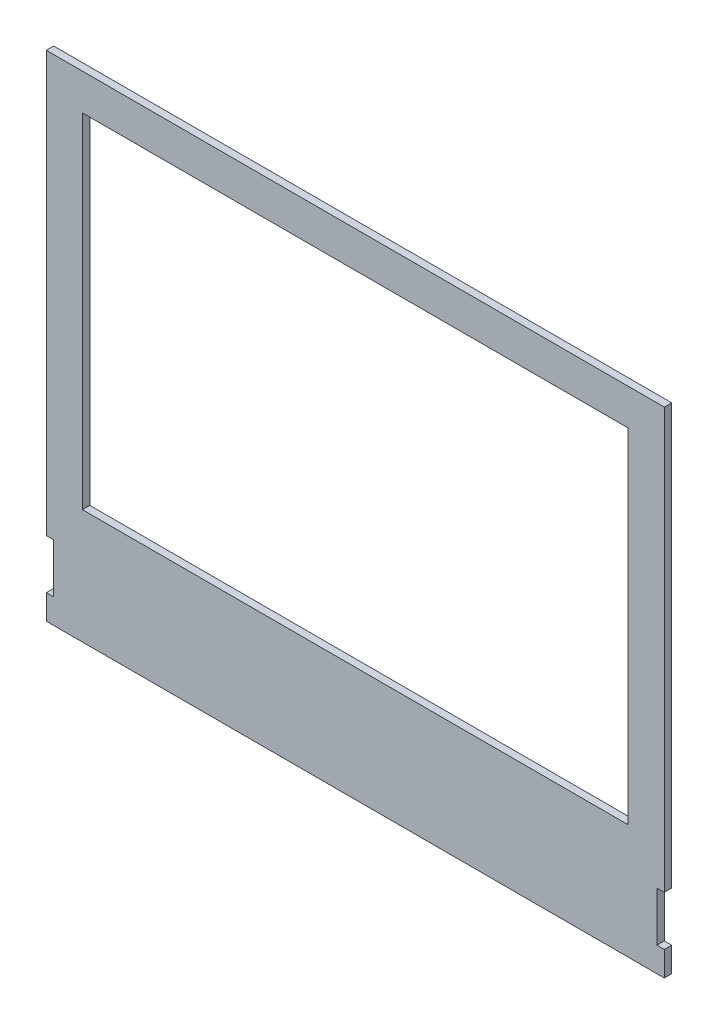
SolidWorks part; units mm, degrees
ref_plane "Front Plane" through (0, 0, 0) normal (0, 0, 1) x (1, 0, 0)
ref_plane "Top Plane" through (0, 0, 0) normal (0, 1, 0) x (1, 0, 0)
ref_plane "Right Plane" through (0, 0, 0) normal (1, 0, 0) x (0, 0, -1)
sketch "Sketch1" plane through (0, 0, 0) normal (0, 0, 1) x (1, 0, 0)
  line L1 (0, 0) -> (250, 0)
  line L2 (0, 0) -> (0, 200)
  line L3 (0, 200) -> (250, 200)
  line L4 (250, 0) -> (250, 200)
  dimension "D1" = 250
  dimension "D2" = 200
extrude "Boss-Extrude1" add sketch "Sketch1" along normal blind 3
sketch "Sketch2" plane through (0, 0, 3) normal (0, 0, 1) x (1, 0, 0)
  line L0 (0, 200) -> (0, 0) construction
  line L1 (14.62, 185.38) -> (235.38, 185.38)
  line L2 (14.62, 185.38) -> (14.62, 46.38)
  line L3 (14.62, 46.38) -> (235.38, 46.38)
  line L4 (235.38, 185.38) -> (235.38, 46.38)
  line L5 (0, 0) -> (250, 0) construction
  line L6 (250, 200) -> (0, 200) construction
  dimension "D1" = 14.62
  dimension "D2" = 220.76
  dimension "D3" = 139
  dimension "D4" = 14.62
  dimension "D5" = 46.38
  dimension "D6" = 153.62
extrude "Cut-Extrude1" cut sketch "Sketch2" against normal through all
sketch "Sketch5" plane through (0, 0, 3) normal (0, 0, 1) x (1, 0, 0)
  line L0 (0, 200) -> (0, 0) construction
  line L1 (0, 10) -> (3, 10)
  line L2 (0, 10) -> (0, 30)
  line L3 (0, 30) -> (3, 30)
  line L4 (3, 10) -> (3, 30)
  line L5 (250, 0) -> (250, 200) construction
  line L6 (250, 30) -> (247, 30)
  line L7 (250, 30) -> (250, 10)
  line L8 (250, 10) -> (247, 10)
  line L9 (247, 30) -> (247, 10)
  line L10 (0, 0) -> (250, 0) construction
  dimension "D1" = 20
  dimension "D2" = 3
  dimension "D3" = 3
  dimension "D4" = 20
  dimension "D5" = 10
  dimension "D6" = 10
extrude "Cut-Extrude3" cut sketch "Sketch5" against normal blind 10
